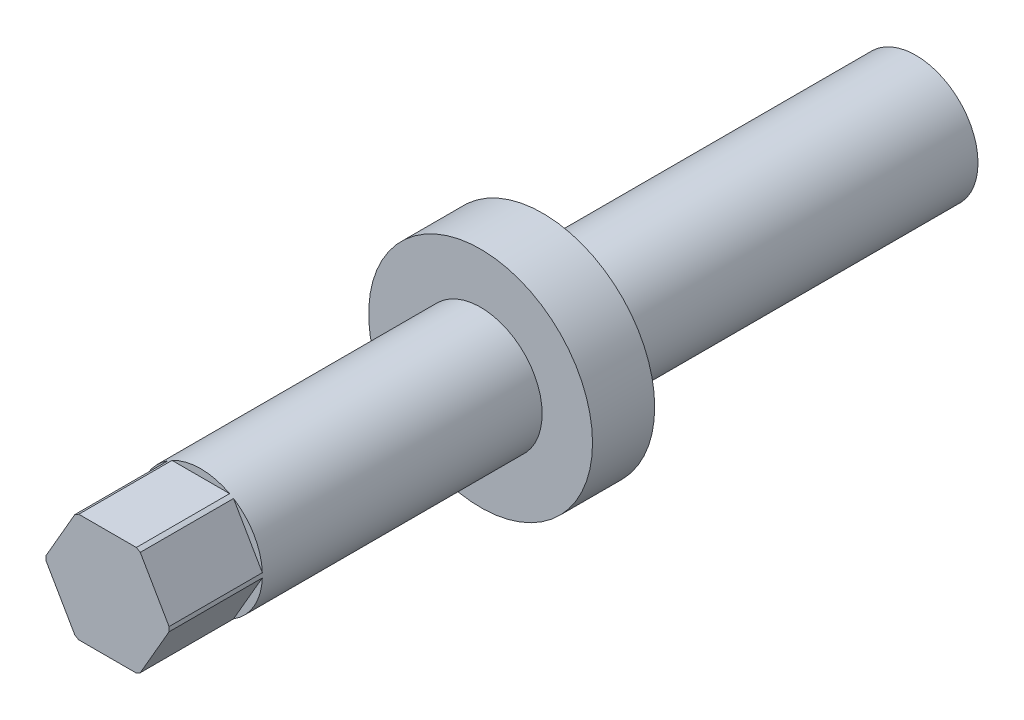
SolidWorks part; units mm, degrees
ref_plane "Front Plane" through (0, 0, 0) normal (0, 0, 1) x (1, 0, 0)
ref_plane "Top Plane" through (0, 0, 0) normal (0, 1, 0) x (1, 0, 0)
ref_plane "Right Plane" through (0, 0, 0) normal (1, 0, 0) x (0, 0, -1)
sketch "Sketch1" plane through (0, 0, 0) normal (1, 0, 0) x (0, 0, -1)
  line L0 (0, 6.2865) -> (0, -6.2865)
  line L1 (0, -6.2865) -> (38.1, -6.2865)
  line L2 (38.1, -6.2865) -> (38.1, -11.43)
  line L3 (38.1, -11.43) -> (44.45, -11.43)
  line L4 (44.45, -11.43) -> (44.45, -6.35)
  line L5 (44.45, -6.35) -> (82.55, -6.35)
  line L6 (82.55, -6.35) -> (82.55, 6.35)
  line L7 (82.55, 6.35) -> (44.45, 6.35)
  line L8 (44.45, 6.35) -> (44.45, 11.43)
  line L9 (44.45, 11.43) -> (38.1, 11.43)
  line L10 (38.1, 11.43) -> (38.1, 6.2865)
  line L11 (38.1, 6.2865) -> (0, 6.2865)
  line L12 (0, 0) -> (82.55, 0) construction
  point P5 (0, 0)
  dimension "D1" = 12.573
  dimension "D2" = 22.86
  dimension "D3" = 12.7
  dimension "D4" = 38.1
  dimension "D5" = 6.35
  dimension "D6" = 38.1
revolve "Revolve2" add sketch "Sketch1" angle 360 about L12
hole_wizard "1/4-20 Tapped Hole1" positions "Sketch2" profile "Sketch3" tap size "1/4-20" standard "ANSI Inch"
sketch "Sketch2" plane through (0, 0, -82.55) normal (0, 0, -1) x (-1, 0, 0)
  point P0 (0, 0)
sketch "Sketch3" plane through (0, 0, -82.55) normal (1, 0, 0) x (0, 1, 0)
  line L0 (0, 0) -> (0, 18.0438)
  line L1 (0, 18.0438) -> (2.5527, 16.51)
  line L2 (2.5527, 16.51) -> (2.5527, 0)
  line L5 (2.5527, 0) -> (0, 0)
  line L10 (0, 18.0438) -> (-2.5527, 16.51) construction
  line L11 (0, -6.35) -> (0, 107.95) construction
  dimension "Tap Drill Dia." = 5.1054
  dimension "Tap Drill Depth" = 16.51
  dimension "Drill Angle" = 118
cosmetic thread "Hole Thread1" parameters "D1"=12.7, "D2"=6.35
sketch "Sketch4" plane through (0, 0, 0) normal (0, 0, 1) x (1, 0, 0)
  line L1 (-6.4158, 0) -> (-3.2079, -5.5562)
  line L2 (-3.2079, -5.5562) -> (3.2079, -5.5562)
  line L3 (3.2079, -5.5562) -> (6.4158, 0)
  line L4 (6.4158, 0) -> (3.2079, 5.5563)
  line L5 (3.2079, 5.5563) -> (-3.2079, 5.5563)
  line L6 (-3.2079, 5.5563) -> (-6.4158, 0)
  circle A0 centre (0, 0) radius 5.5562 construction
  circle A2 centre (0, 0) radius 6.2865 construction
  circle A3 centre (0, 0) radius 6.2865
  circle M8 centre (0, 0) radius 6.2865
  dimension "D1" = 11.1125
extrude "Cut-Extrude1" cut sketch "Sketch4" against normal blind 9.525 contours L5 M8 | L4 M8 | L3 M8 | L2 M8 | L1 M8 | L6 M8
